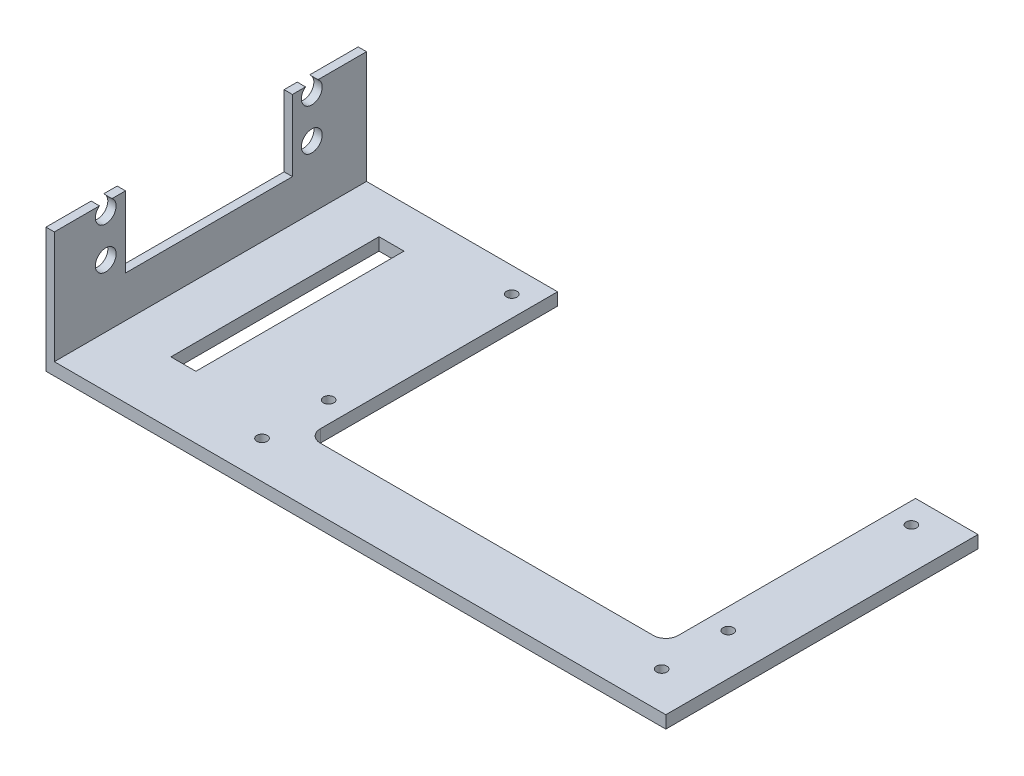
SolidWorks part; units mm, degrees
material "6063-T5"
ref_plane "前视基准面" through (0, 0, 0) normal (0, 0, 1) x (1, 0, 0)
ref_plane "上视基准面" through (0, 0, 0) normal (0, 1, 0) x (1, 0, 0)
ref_plane "右视基准面" through (0, 0, 0) normal (1, 0, 0) x (0, 0, -1)
other "Configuration Table"
sketch "草图1" plane through (0, 0, 0) normal (0, 1, 0) x (1, 0, 0)
  line L0 (0, 0) -> (0, 60)
  line L1 (0, 60) -> (-15, 60)
  line L2 (-15, 60) -> (-15, -15)
  line L3 (-15, -15) -> (101, -15)
  line L4 (101, -15) -> (101, 60)
  line L5 (101, 60) -> (86, 60)
  line L6 (86, 60) -> (86, 0)
  line L7 (86, 0) -> (0, 0)
  line L8 (0, 30) -> (59.3, 30) construction
  line L9 (59.3, 30) -> (0, 30) construction
  line L10 (43, 78.0523) -> (43, -12.0435) construction
  circle A0 centre (-5, 54) radius 1.25
  circle A1 centre (-5, -6) radius 1.25
  circle A2 centre (91, 54) radius 1.25
  circle A3 centre (91, -6) radius 1.25
  circle A4 centre (91, 10) radius 1.25
  circle A5 centre (-5, 10) radius 1.25
  dimension "D8" = 2.5
  dimension "2.5" = 2.5
  dimension "D11" = 2.5
  dimension "D17" = 5
  dimension "D18" = 2.5
  dimension "D19" = 5
  dimension "D20" = 5
  dimension "D21" = 5
  dimension "D22" = 2.5
  dimension "D1" = 75
  dimension "D2" = 15
  dimension "D3" = 15
  dimension "D4" = 15
  dimension "D5" = 75
  dimension "D6" = 86
  dimension "D7" = 6
  dimension "D9" = 6
  dimension "D12" = 44
  dimension "D13" = 9
  dimension "D14" = 9
  dimension "D15" = 25
  dimension "D16" = 5
extrude "凸台-拉伸1" add sketch "草图1" along normal blind 3
fillet "圆角1" radius 3 2 edges at (86, 1.5, 0) (0, 1.5, 0)
sketch "草图2" plane through (-15, 0, 0) normal (-1, 0, 0) x (0, 0, 1)
  line L4 (-60, 0) -> (15, 0)
  line L5 (15, 0) -> (15, 3)
  line L6 (15, 3) -> (-60, 3)
  line L7 (-60, 3) -> (-60, 0)
  line L8 (-60, 0) -> (15, 0)
  line L9 (15, 0) -> (15, 3)
  line L10 (15, 3) -> (-60, 3)
  line L11 (-60, 3) -> (-60, 0)
  dimension "D1" = 0
extrude "凸台-拉伸2" add sketch "草图2" along normal up to surface (32.9 mm away)
sketch "草图3" plane through (0, 3, 0) normal (0, 1, 0) x (1, 0, 0)
  line L0 (-47.9, -15) -> (-47.9, 60) construction
  line L1 (-47.9, 60) -> (-45.9, 60)
  line L2 (-47.9, 60) -> (-47.9, -15)
  line L3 (-47.9, -15) -> (-45.9, -15)
  line L4 (-45.9, 60) -> (-45.9, -15)
  line L5 (0, 60) -> (-47.9, 60) construction
  line L6 (-47.9, -15) -> (101, -15) construction
  dimension "D1" = 2
extrude "凸台-拉伸4" add sketch "草图3" along normal blind 30
sketch "草图5" plane through (-45.9, 0, 0) normal (1, 0, 0) x (0, 0, -1)
  line L0 (-15, 33) -> (60, 33) construction
  line L1 (42.2, 33) -> (2.1, 33)
  line L2 (42.2, 33) -> (42.2, 12.9)
  line L3 (42.2, 12.9) -> (2.1, 12.9)
  line L4 (2.1, 33) -> (2.1, 12.9)
  line L5 (60, 33) -> (60, 0) construction
  dimension "D1" = 40.1
  dimension "D2" = 17.8
  dimension "D3" = 20.1
extrude "切除-拉伸1" cut sketch "草图5" against normal up to next
sketch "草图6" plane through (-47.9, 0, 0) normal (-1, 0, 0) x (0, 0, 1)
  circle A0 centre (-46.85, 18) radius 2.5
  circle A1 centre (-46.85, 28) radius 2.5
  circle A2 centre (2.65, 18) radius 2.5
  circle A3 centre (2.65, 28) radius 2.5
extrude "切除-拉伸2" cut sketch "草图6" against normal up to next
sketch "草图7" plane through (0, 33, 0) normal (0, 1, 0) x (1, 0, 0)
  line L0 (-47.9, 60) -> (-45.9, 60)
  line L1 (-45.9, 60) -> (-45.9, -15)
  line L2 (-45.9, -15) -> (-47.9, -15)
  line L3 (-47.9, -15) -> (-47.9, 60)
extrude "切除-拉伸3" cut sketch "草图7" against normal blind 3
sketch "草图9" plane through (0, 3, 0) normal (0, 1, 0) x (1, 0, 0)
  line L0 (-45.9, 48.35) -> (-45.9, 60) construction
  line L1 (-32.9, 50) -> (-26.9, 50)
  line L2 (-32.9, 50) -> (-32.9, 0)
  line L3 (-32.9, 0) -> (-26.9, 0)
  line L4 (-26.9, 50) -> (-26.9, 0)
  line L5 (0, 60) -> (-45.9, 60) construction
  dimension "D1" = 13
  dimension "D2" = 6
  dimension "D3" = 10
  dimension "D4" = 50
extrude "切除-拉伸4" cut sketch "草图9" against normal through all
